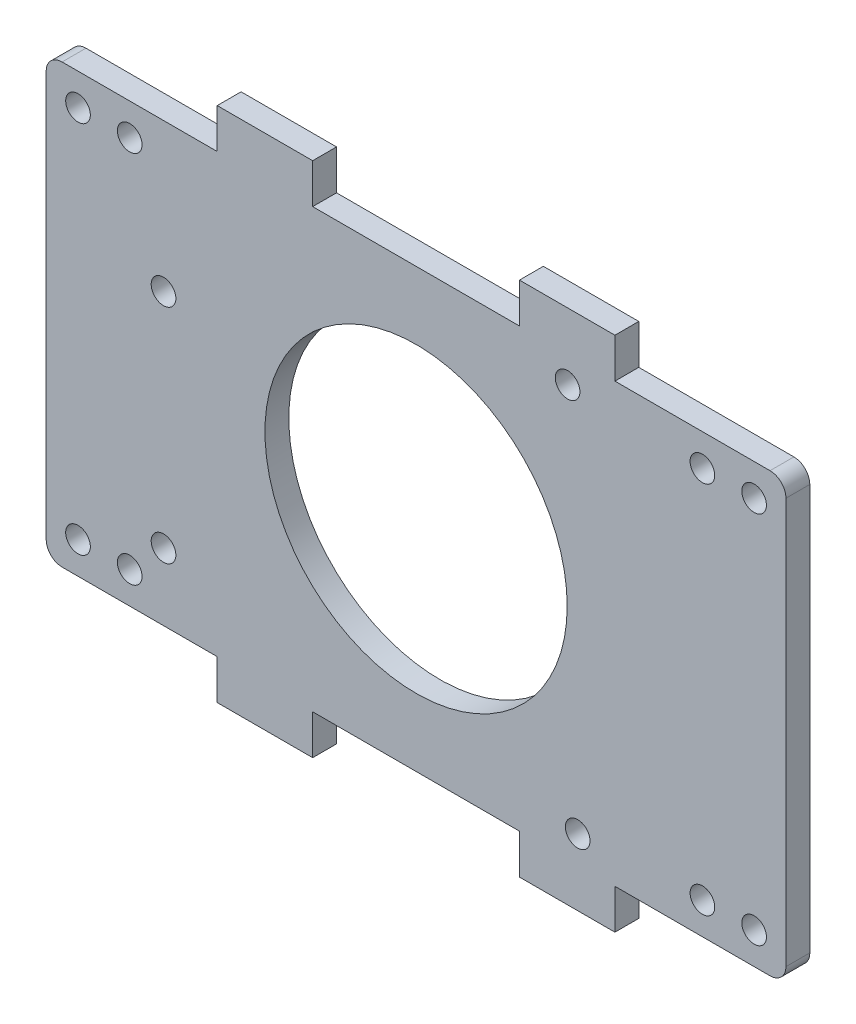
SolidWorks part; units mm, degrees
ref_plane "Plan de face" through (0, 0, 0) normal (0, 0, 1) x (1, 0, 0)
ref_plane "Plan de dessus" through (0, 0, 0) normal (0, 1, 0) x (1, 0, 0)
ref_plane "Plan de droite" through (0, 0, 0) normal (1, 0, 0) x (0, 0, -1)
sketch "Esquisse1" plane through (0, 0, 0) normal (0, 0, 1) x (1, 0, 0)
  line L0 (-25, -32.5) -> (-25, -27.5)
  line L1 (-44.5, -27.5) -> (-25, -27.5)
  line L2 (-46.5, 25.5) -> (-46.5, -25.5)
  line L3 (-42.5, 23.5) -> (42.5, 23.5) construction
  line L4 (-25, 27.5) -> (-44.5, 27.5)
  line L5 (-25, 32.5) -> (-25, 27.5)
  line L6 (-25, 32.5) -> (-13, 32.5)
  line L7 (-13, 27.5) -> (-13, 32.5)
  line L8 (-13, 27.5) -> (13, 27.5)
  line L9 (13, 27.5) -> (13, 32.5)
  line L10 (13, 32.5) -> (25, 32.5)
  line L11 (25, 32.5) -> (25, 27.5)
  line L12 (44.5, 27.5) -> (25, 27.5)
  line L13 (42.5, 23.5) -> (42.5, -23.5) construction
  line L14 (46.5, -25.5) -> (46.5, 25.5)
  line L15 (25, -27.5) -> (44.5, -27.5)
  line L16 (25, -32.5) -> (25, -27.5)
  line L17 (13, -32.5) -> (25, -32.5)
  line L18 (13, -27.5) -> (13, -32.5)
  line L19 (-13, -27.5) -> (13, -27.5)
  line L20 (-13, -27.5) -> (-13, -32.5)
  line L21 (-25, -32.5) -> (-13, -32.5)
  line L22 (42.5, -23.5) -> (-42.5, -23.5) construction
  line L23 (-42.5, -23.5) -> (-42.5, 23.5) construction
  arc A0 (-46.5, -25.5) -> (-44.5, -27.5) centre (-44.5, -25.5) ccw
  arc A1 (-44.5, 27.5) -> (-46.5, 25.5) centre (-44.5, 25.5) ccw
  arc A2 (46.5, 25.5) -> (44.5, 27.5) centre (44.5, 25.5) ccw
  arc A3 (44.5, -27.5) -> (46.5, -25.5) centre (44.5, -25.5) ccw
  circle A4 centre (0, 0) radius 19
  circle A25 centre (-42.5, 23.5) radius 1.55
  circle A26 centre (-36, 23.5) radius 1.55
  circle A27 centre (-31.75, 8.89) radius 1.55
  circle A28 centre (-31.75, -19.05) radius 1.55
  circle A29 centre (-36, -23.5) radius 1.55
  circle A30 centre (-42.5, -23.5) radius 1.55
  circle A31 centre (19.05, 24.13) radius 1.55
  circle A32 centre (36, 23.5) radius 1.55
  circle A33 centre (42.5, 23.5) radius 1.55
  circle A34 centre (42.5, -23.5) radius 1.55
  circle A35 centre (36, -23.5) radius 1.55
  circle A36 centre (20.32, -24.13) radius 1.55
  dimension "D1" = 93
  dimension "D2" = 38
  dimension "D13" = 2
  dimension "D18" = 48.26
  dimension "D19" = 4
  dimension "D20" = 4
  dimension "D23" = 3.1
  dimension "D24" = 6.5
  dimension "D25" = 6.5
  dimension "D26" = 6.5
  dimension "D27" = 6.5
  dimension "D28" = 10.75
  dimension "D29" = 10.75
  dimension "D30" = 4.45
  dimension "D31" = 27.94
  dimension "D32" = 20.32
  dimension "D3" = 55
  dimension "D4" = 27.5
  dimension "D5" = 46.5
  dimension "D6" = 21.5
  dimension "D7" = 12
  dimension "D8" = 26
  dimension "D9" = 12
  dimension "D10" = 5
  dimension "D11" = 5
  dimension "D12" = 2
  dimension "D14" = 2
  dimension "D15" = 2
  dimension "D16" = 2
  dimension "D17" = 2
  dimension "D21" = 8
  dimension "D22" = 47
extrude "Boss.-Extru.1" add sketch "Esquisse1" along normal blind 3
